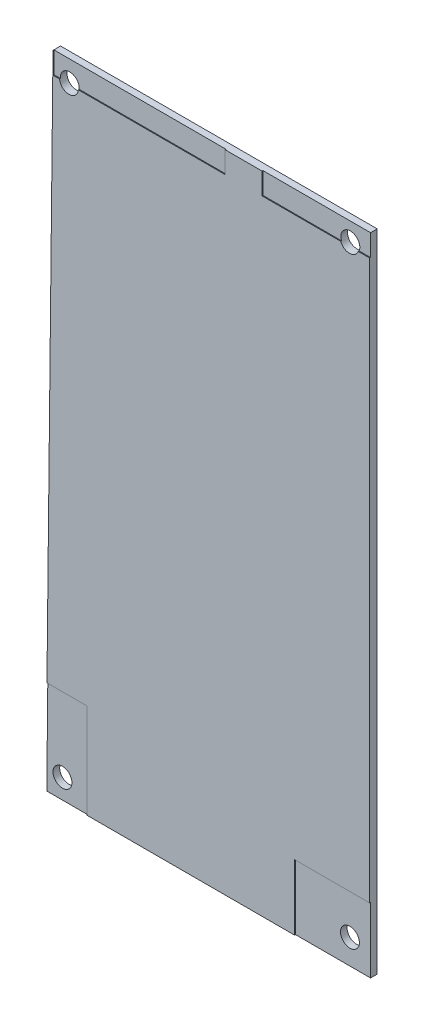
SolidWorks part; units mm, degrees
ref_plane "Alzado" through (0, 0, 0) normal (0, 0, 1) x (1, 0, 0)
ref_plane "Planta" through (0, 0, 0) normal (0, 1, 0) x (1, 0, 0)
ref_plane "Vista lateral" through (0, 0, 0) normal (1, 0, 0) x (0, 0, -1)
sketch "Croquis1" plane through (0, 0, 0) normal (0, 0, 1) x (1, 0, 0)
  line L0 (0, 0) -> (75.25, 0)
  line L1 (75.25, 0) -> (75.25, 150)
  line L2 (75.25, 150) -> (1.65, 150)
  line L3 (1.65, 150) -> (0, 0)
  dimension "D1" = 150
  dimension "D2" = 73.6
  dimension "D3" = 75.25
extrude "Saliente-Extruir1" add sketch "Croquis1" along normal blind 1.75
sketch "Croquis2" plane through (0, 0, 1.75) normal (0, 0, 1) x (1, 0, 0)
  line L1 (75.25, 0) -> (57.75, 0)
  line L2 (75.25, 0) -> (75.25, 15.2)
  line L3 (75.25, 15.2) -> (57.75, 15.2)
  line L4 (57.75, 0) -> (57.75, 15.2)
  line L5 (0, 0) -> (9.5, 0)
  line L6 (0, 0) -> (0, 22)
  line L7 (0, 22) -> (9.5, 22)
  line L8 (9.5, 0) -> (9.5, 22)
  line L9 (1.65, 150) -> (41.65, 150)
  line L10 (1.65, 150) -> (1.65, 145)
  line L11 (1.65, 145) -> (41.65, 145)
  line L12 (41.65, 150) -> (41.65, 145)
  line L13 (75.25, 150) -> (50.25, 150)
  line L14 (75.25, 150) -> (75.25, 145)
  line L15 (75.25, 145) -> (50.25, 145)
  line L16 (50.25, 150) -> (50.25, 145)
  dimension "D1" = 17.5
  dimension "D2" = 15.2
  dimension "D3" = 9.5
  dimension "D4" = 22
  dimension "D5" = 40
  dimension "D6" = 25
  dimension "D7" = 5
extrude "Cortar-Extruir1" cut sketch "Croquis2" against normal blind 0.2
sketch "Croquis3" plane through (0, 0, 1.55) normal (0, 0, 1) x (1, 0, 0)
  line L1 (0, 0) -> (0.242, 22) construction
  line L2 (0, 0) -> (9.5, 0) construction
  line L4 (57.75, 0) -> (75.25, 0) construction
  line L5 (75.25, 0) -> (75.25, 15.2) construction
  line L6 (75.25, 145) -> (75.25, 150) construction
  line L7 (75.25, 150) -> (50.25, 150) construction
  line L8 (41.65, 150) -> (1.65, 150) construction
  line L10 (1.65, 150) -> (1.65, 145) construction
  circle A0 centre (3.6508, 4.6) radius 2.2
  circle A1 centre (70.45, 5.8) radius 2.2
  circle A2 centre (5.35, 145.2) radius 2.2
  circle A3 centre (70.55, 145.8) radius 2.2
  dimension "D1" = 4.4
  dimension "D6" = 4.4
  dimension "D9" = 4.4
  dimension "D10" = 4.4
  dimension "D12" = 3.7
  dimension "D2" = 3.6
  dimension "D3" = 4.6
  dimension "D4" = 4.8
  dimension "D5" = 5.8
  dimension "D7" = 4.7
  dimension "D8" = 4.2
  dimension "D11" = 4.8
extrude "Cortar-Extruir2" cut sketch "Croquis3" against normal through all both and the other way through all
sketch "Croquis6" plane through (0, 0, 1.75) normal (0, 0, 1) x (1, 0, 0)
  line L0 (70.45, 5.8) -> (70.55, 145.8)
  line L1 (70.55, 145.8) -> (5.35, 145.2)
  line L2 (5.35, 145.2) -> (3.6508, 4.6)
  line L3 (3.6508, 4.6) -> (70.45, 5.8)
  circle A0 centre (5.35, 145.2) radius 2.2 construction
  circle A1 centre (5.35, 145.2) radius 2.2
  circle A2 centre (3.6508, 4.6) radius 2.2 construction
  circle A3 centre (70.45, 5.8) radius 2.2 construction
  circle A4 centre (70.55, 145.8) radius 2.2 construction
  circle A5 centre (3.6508, 4.6) radius 2.2
  circle A6 centre (70.45, 5.8) radius 2.2
  circle A7 centre (70.55, 145.8) radius 2.2
